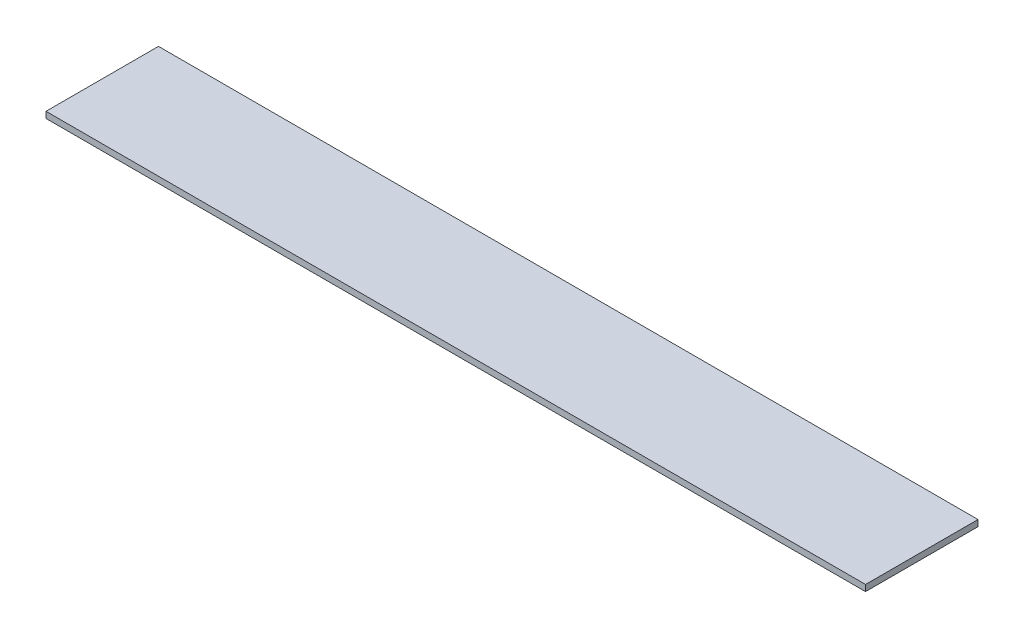
SolidWorks part; units mm, degrees
material "ABS PC"
ref_plane "X-Y Datum" through (0, 0, 0) normal (0, 0, 1) x (1, 0, 0)
ref_plane "X-Z Datum" through (0, 0, 0) normal (0, 1, 0) x (1, 0, 0)
ref_plane "Y-Z Datum" through (0, 0, 0) normal (1, 0, 0) x (0, 0, -1)
sketch "Sketch1" plane through (0, 0, 0) normal (0, 1, 0) x (1, 0, 0)
  line L0 (-199.6499, 39.3901) -> (217.8651, 39.3901)
  line L1 (-199.6499, 39.3901) -> (-199.6499, -17.9099)
  line L2 (-199.6499, -17.9099) -> (217.8651, -17.9099)
  line L3 (217.8651, 39.3901) -> (217.8651, -17.9099)
extrude "Boss-Extrude1" add sketch "Sketch1" along normal blind 3.175
